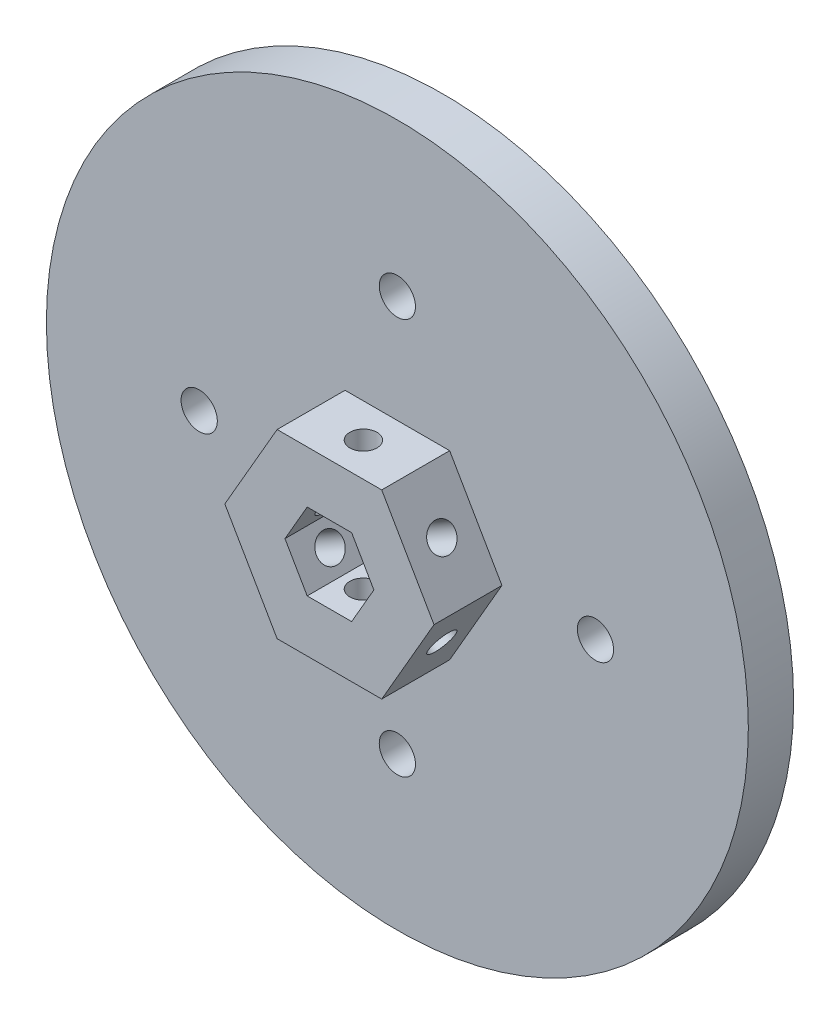
SolidWorks part; units mm, degrees
ref_plane "Płaszczyzna przednia" through (0, 0, 0) normal (0, 0, 1) x (1, 0, 0)
ref_plane "Płaszczyzna górna" through (0, 0, 0) normal (0, 1, 0) x (1, 0, 0)
ref_plane "Płaszczyzna prawa" through (0, 0, 0) normal (1, 0, 0) x (0, 0, -1)
sketch "Szkic1" plane through (0, 0, 0) normal (0, 0, 1) x (1, 0, 0)
  circle A1 centre (0, 0) radius 31
  dimension "D1" = 62
extrude "Dodanie-wyciągnięcie1" add sketch "Szkic1" along normal blind 4
sketch "Szkic2" plane through (0, 0, 4) normal (0, 0, 1) x (1, 0, 0)
  line L1 (4.6188, 8) -> (-4.6188, 8)
  line L2 (-4.6188, 8) -> (-9.2376, 0)
  line L3 (-9.2376, 0) -> (-4.6188, -8)
  line L4 (-4.6188, -8) -> (4.6188, -8)
  line L5 (4.6188, -8) -> (9.2376, 0)
  line L6 (9.2376, 0) -> (4.6188, 8)
  line L7 (1.963, 3.4) -> (-1.963, 3.4)
  line L8 (-1.963, 3.4) -> (-3.926, 0)
  line L9 (-3.926, 0) -> (-1.963, -3.4)
  line L10 (-1.963, -3.4) -> (1.963, -3.4)
  line L11 (1.963, -3.4) -> (3.926, 0)
  line L12 (3.926, 0) -> (1.963, 3.4)
  circle A0 centre (0, 0) radius 8 construction
  circle A1 centre (0, 0) radius 3.4 construction
  dimension "D1" = 6.8
  dimension "D2" = 16
extrude "Dodanie-wyciągnięcie2" add sketch "Szkic2" along normal blind 6
sketch "Szkic3" plane through (0, 8, 0) normal (0, 1, 0) x (1, 0, 0)
  line L0 (4.6188, -4) -> (-4.6188, -4) construction
  line L1 (4.6188, -10) -> (4.6188, -4) construction
  circle A0 centre (0, -7) radius 1.2
  point P4 (0, -4)
  point P7 (4.6188, -7)
  dimension "D1" = 2.4
extrude "Wytnij-wyciągnięcie1" cut sketch "Szkic3" against normal through all
pattern_circular "Szyk kołowy1" count 3 over 360 about axis through (0, 0, 4) along (0, 0, 1) of "Wytnij-wyciągnięcie1"
sketch "Szkic4" plane through (0, 0, 4) normal (0, 0, 1) x (1, 0, 0)
  line L0 (0, 31) -> (0, 0) construction
  line L1 (0, 0) -> (31, 0) construction
  circle A0 centre (0, 0) radius 31 construction
  circle A1 centre (0, 17.5) radius 1.6
  circle A2 centre (17.5, 0) radius 1.6
  circle A3 centre (0, -17.5) radius 1.6
  circle A4 centre (-17.5, 0) radius 1.6
  dimension "D1" = 3.2
  dimension "D2" = 35
  dimension "D3" = 35
extrude "Wytnij-wyciągnięcie2" cut sketch "Szkic4" against normal blind 6
sketch "Szkic5" plane through (0, 0, 4) normal (0, 0, 1) x (1, 0, 0)
  line L6 (3.926, 0) -> (1.963, 3.4)
  line L7 (1.963, 3.4) -> (-1.963, 3.4)
  line L8 (-1.963, 3.4) -> (-3.926, 0)
  line L9 (-3.926, 0) -> (-1.963, -3.4)
  line L10 (-1.963, -3.4) -> (1.963, -3.4)
  line L11 (1.963, -3.4) -> (3.926, 0)
  line L12 (3.926, 0) -> (1.963, 3.4)
  line L13 (1.963, 3.4) -> (-1.963, 3.4)
  line L14 (-1.963, 3.4) -> (-3.926, 0)
  line L15 (-3.926, 0) -> (-1.963, -3.4)
  line L16 (-1.963, -3.4) -> (1.963, -3.4)
  line L17 (1.963, -3.4) -> (3.926, 0)
  dimension "D1" = 0
extrude "Wytnij-wyciągnięcie3" cut sketch "Szkic5" against normal through all
